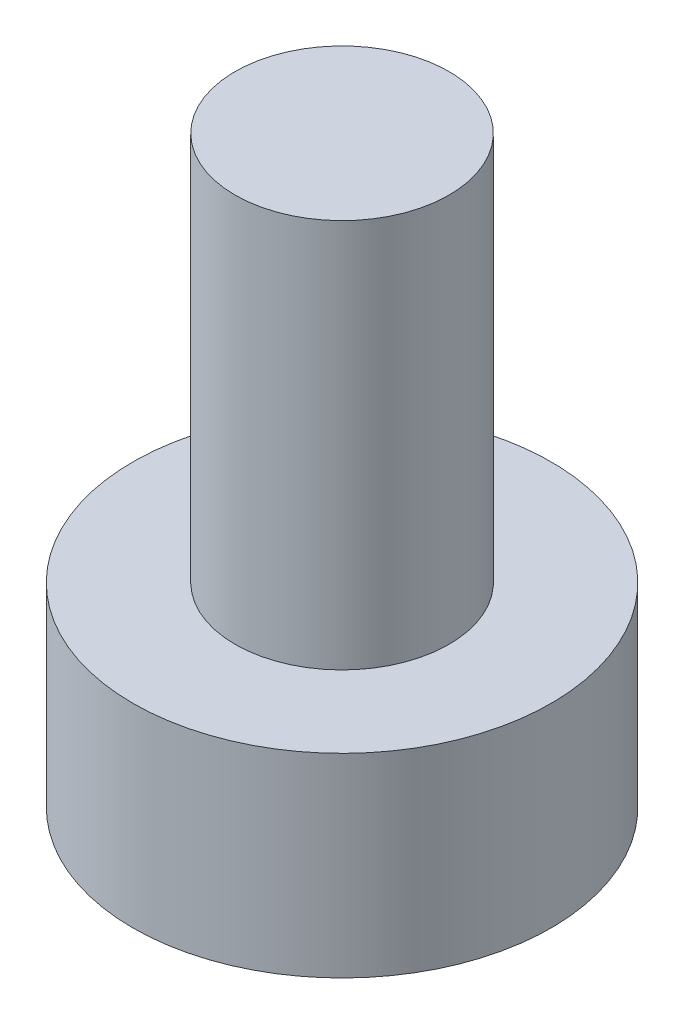
SolidWorks part; units mm, degrees
ref_plane "Front Plane" through (0, 0, 0) normal (0, 0, 1) x (1, 0, 0)
ref_plane "Top Plane" through (0, 0, 0) normal (0, 1, 0) x (1, 0, 0)
ref_plane "Right Plane" through (0, 0, 0) normal (1, 0, 0) x (0, 0, -1)
sketch "Sketch1" plane through (0, 0, 0) normal (0, 1, 0) x (1, 0, 0)
  circle A0 centre (0, 0) radius 2.15
  dimension "D1" = 4.3
extrude "Boss-Extrude1" add sketch "Sketch1" along normal blind 2
sketch "Sketch2" plane through (0, 2, 0) normal (0, 1, 0) x (1, 0, 0)
  circle A0 centre (0, 0) radius 1.1
  dimension "D1" = 2.2
extrude "Boss-Extrude2" add sketch "Sketch2" along normal blind 4
